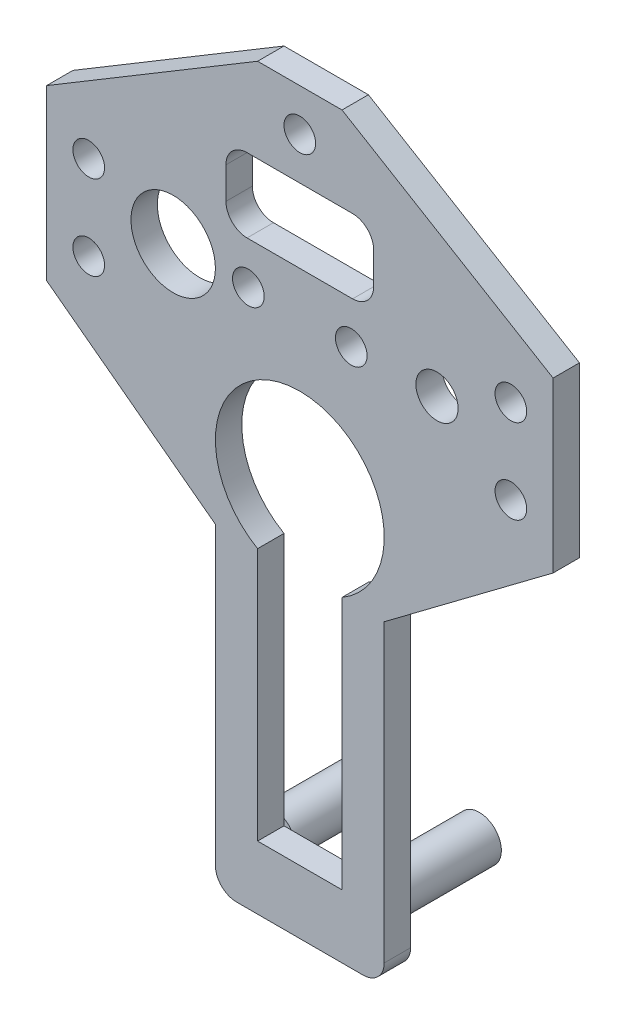
SolidWorks part; units mm, degrees
ref_plane "Front Plane" through (0, 0, 0) normal (0, 0, 1) x (1, 0, 0)
ref_plane "Top Plane" through (0, 0, 0) normal (0, 1, 0) x (1, 0, 0)
ref_plane "Right Plane" through (0, 0, 0) normal (1, 0, 0) x (0, 0, -1)
sketch "Sketch1" plane through (0, 0, 0) normal (0, 0, 1) x (1, 0, 0)
  line L0 (-24, 5.0718) -> (-24, 21.0718)
  line L1 (-24, 21.0718) -> (-4, 33.0718)
  line L2 (-4, 33.0718) -> (4, 33.0718)
  line L3 (4, 33.0718) -> (24, 21.0718)
  line L4 (24, 21.0718) -> (24, 5.0718)
  line L5 (24, 5.0718) -> (8, -6.9282)
  line L6 (8, -6.9282) -> (8, -34.9282)
  line L7 (-6, -36.9282) -> (6, -36.9282)
  line L8 (-8, -34.9282) -> (-8, -6.9282)
  line L9 (-8, -6.9282) -> (-24, 5.0718)
  line L10 (4, -30.9282) -> (-4, -30.9282)
  line L11 (-4, -30.9282) -> (-4, -6.9282)
  line L12 (4, -6.9282) -> (4, -30.9282)
  line L13 (-5, 25.0718) -> (5, 25.0718)
  line L14 (7, 23.0718) -> (7, 20.0718)
  line L15 (-7, 23.0718) -> (-7, 20.0718)
  line L16 (-5, 18.0718) -> (5, 18.0718)
  arc A0 (-4, -6.9282) -> (4, -6.9282) centre (0, 0) cw
  arc A1 (5, 25.0718) -> (7, 23.0718) centre (5, 23.0718) cw
  arc A2 (-5, 25.0718) -> (-7, 23.0718) centre (-5, 23.0718) ccw
  arc A3 (-7, 20.0718) -> (-5, 18.0718) centre (-5, 20.0718) ccw
  arc A4 (5, 18.0718) -> (7, 20.0718) centre (5, 20.0718) ccw
  circle A5 centre (-12, 14.0718) radius 4
  circle A6 centre (-4.875, 14.0718) radius 1.5
  circle A7 centre (4.875, 14.0718) radius 1.5
  circle A8 centre (0, 29.0718) radius 1.5
  circle A9 centre (20, 17.0718) radius 1.5
  circle A10 centre (20, 9.0718) radius 1.5
  circle A11 centre (-20, 17.0718) radius 1.5
  circle A12 centre (-20, 9.0718) radius 1.5
  circle A13 centre (13, 14.0718) radius 2
  arc A14 (-8, -34.9282) -> (-6, -36.9282) centre (-6, -34.9282) ccw
  arc A15 (6, -36.9282) -> (8, -34.9282) centre (6, -34.9282) ccw
  dimension "D1" = 28
  dimension "D4" = 12
  dimension "D7" = 4
  dimension "D8" = 4
  dimension "D9" = 2
  dimension "D10" = 8
  dimension "D19" = 8
  dimension "D20" = 10
  dimension "D22" = 2
  dimension "D18" = 8
  dimension "D24" = 3
  dimension "D25" = 4
  dimension "D31" = 4
  dimension "D3" = 8
  dimension "D5" = 8
  dimension "D6" = 24
  dimension "D11" = 6
  dimension "D12" = 16
  dimension "D13" = 17
  dimension "D14" = 20
  dimension "D15" = 48
  dimension "D16" = 24
  dimension "D17" = 19.125
  dimension "D21" = 3
  dimension "D23" = 12
  dimension "D26" = 4
  dimension "D27" = 4
  dimension "D28" = 4
  dimension "D29" = 4
  dimension "D30" = 4
  dimension "D32" = 19.125
  dimension "D33" = 70
  dimension "D34" = 24
  dimension "D35" = 120.964
  dimension "D36" = 11
extrude "Boss-Extrude1" add sketch "Sketch1" along normal blind 2.5
sketch "Sketch2" plane through (0, 0, 0) normal (0, 0, -1) x (-1, 0, 0)
  line L0 (-5, -32.1616) -> (5, -32.1616) construction
  circle A0 centre (-5, -32.1616) radius 2.1
  circle A2 centre (5, -32.1616) radius 2.1
extrude "Boss-Extrude2" add sketch "Sketch2" along normal blind 9.5
